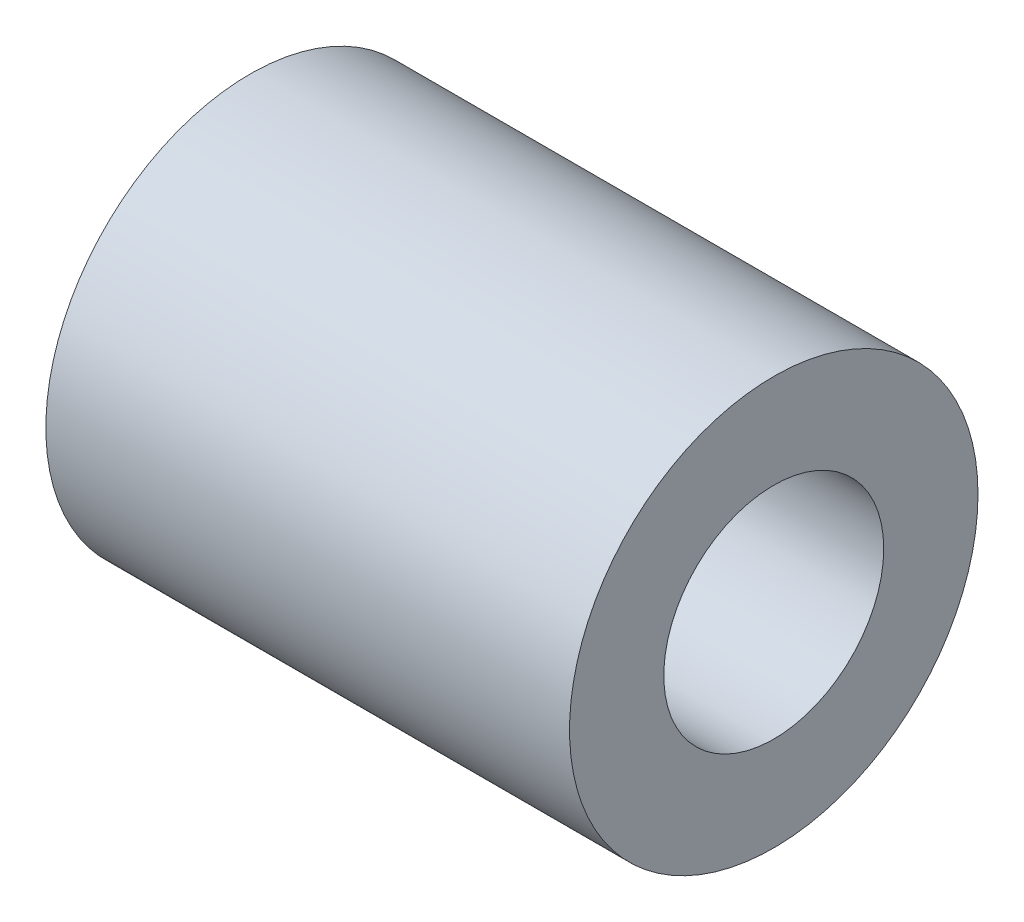
SolidWorks part; units mm, degrees
ref_plane "Front Plane" through (0, 0, 0) normal (0, 0, 1) x (1, 0, 0)
ref_plane "Top Plane" through (0, 0, 0) normal (0, 1, 0) x (1, 0, 0)
ref_plane "Right Plane" through (0, 0, 0) normal (1, 0, 0) x (0, 0, -1)
sketch "Sketch1" plane through (0, 0, 0) normal (1, 0, 0) x (0, 0, -1)
  circle A0 centre (0, 0) radius 3.15
  circle A1 centre (0, 0) radius 5.85
  dimension "D1" = 6.3
  dimension "D2" = 11.7
extrude "Boss-Extrude1" add sketch "Sketch1" along normal blind 15
